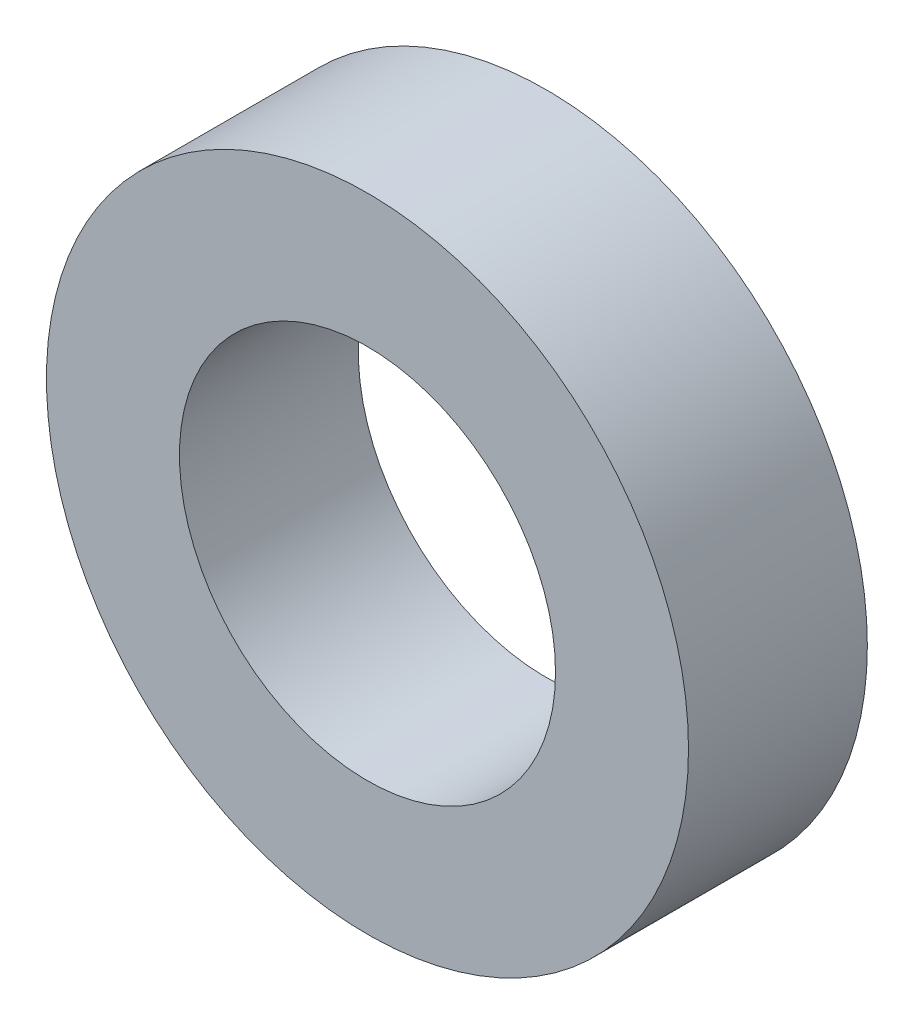
SolidWorks part; units mm, degrees
ref_plane "Front Plane" through (0, 0, 0) normal (0, 0, 1) x (1, 0, 0)
ref_plane "Top Plane" through (0, 0, 0) normal (0, 1, 0) x (1, 0, 0)
ref_plane "Right Plane" through (0, 0, 0) normal (1, 0, 0) x (0, 0, -1)
sketch "Sketch1" plane through (0, 0, 0) normal (0, 0, 1) x (1, 0, 0)
  circle A0 centre (0, 0) radius 14.224
extrude "Boss-Extrude1" add sketch "Sketch1" along normal blind 7.9248
sketch "Sketch2" plane through (0, 0, 0) normal (0, 0, 1) x (1, 0, 0)
  circle A0 centre (0, 0) radius 8.3312
extrude "Cut-Extrude1" cut sketch "Sketch2" along normal through all
